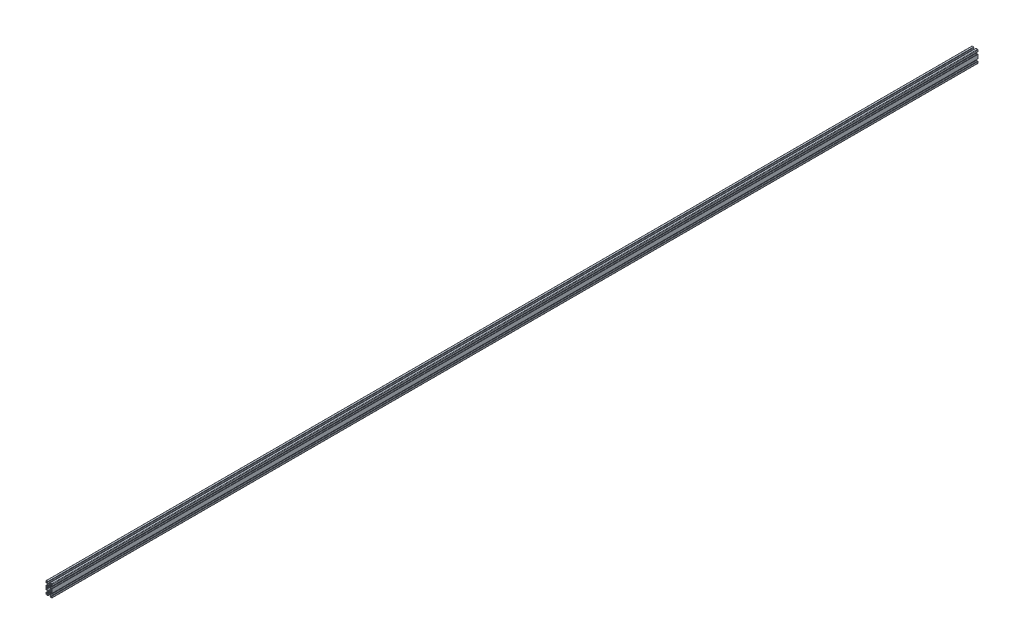
SolidWorks part; units mm, degrees
material "6061 Alloy"
ref_plane "Front Plane" through (0, 0, 0) normal (0, 0, 1) x (1, 0, 0)
ref_plane "Top Plane" through (0, 0, 0) normal (0, 1, 0) x (1, 0, 0)
ref_plane "Right Plane" through (0, 0, 0) normal (1, 0, 0) x (0, 0, -1)
sketch "Sketch1" plane through (0, 0, 0) normal (0, 0, 1) x (1, 0, 0)
  line L0 (10, -3.75) -> (10, -8.5)
  line L1 (8.5, -3.55) -> (8.5, -5.5)
  line L2 (9.5, -3.25) -> (9.5, -3.35)
  line L3 (9.7, -3.55) -> (9.8, -3.55)
  line L4 (9, -3.05) -> (9.3, -3.05)
  line L5 (9.7, 3.45) -> (9.8, 3.45)
  line L6 (9.5, 3.15) -> (9.5, 3.25)
  line L7 (9, 2.95) -> (9.3, 2.95)
  line L8 (8.5, 3.45) -> (8.5, 5.5)
  line L9 (10, 3.65) -> (10, 10)
  line L10 (-9.7, 3.45) -> (-9.8, 3.45)
  line L11 (-9.5, 3.15) -> (-9.5, 3.25)
  line L12 (-9, 2.95) -> (-9.3, 2.95)
  line L13 (-8.5, 3.45) -> (-8.5, 5.5)
  line L14 (-10, 3.65) -> (-10, 10)
  line L15 (-9.7, -3.55) -> (-9.8, -3.55)
  line L16 (-9.5, -3.25) -> (-9.5, -3.35)
  line L17 (-9, -3.05) -> (-9.3, -3.05)
  line L18 (-8.5, -3.55) -> (-8.5, -5.5)
  line L19 (-10, -3.75) -> (-10, -8.5)
  line L20 (-3.7, -10) -> (-8.5, -10)
  line L21 (-3.5, -8.5) -> (-5.5, -8.5)
  line L22 (-3.2, -9.5) -> (-3.3, -9.5)
  line L23 (-3.5, -9.7) -> (-3.5, -9.8)
  line L24 (-3, -9) -> (-3, -9.3)
  line L25 (3.7, -10) -> (8.5, -10)
  line L26 (3.5, -9.7) -> (3.5, -9.8)
  line L27 (3.2, -9.5) -> (3.3, -9.5)
  line L28 (3, -9) -> (3, -9.3)
  line L29 (3.5, -8.5) -> (5.5, -8.5)
  line L30 (-9.7, 23.5) -> (-9.8, 23.5)
  line L31 (-9.5, 23.2) -> (-9.5, 23.3)
  line L32 (-9, 23) -> (-9.3, 23)
  line L33 (-8.5, 23.5) -> (-8.5, 25.55)
  line L34 (-10, 23.7) -> (-10, 28.5)
  line L35 (-9.7, 16.5) -> (-9.8, 16.5)
  line L36 (-9.5, 16.8) -> (-9.5, 16.7)
  line L37 (-9, 17) -> (-9.3, 17)
  line L38 (-8.5, 16.5) -> (-8.5, 14.55)
  line L39 (-10, 16.3) -> (-10, 10)
  line L40 (10, 16.3) -> (10, 10)
  line L41 (8.5, 16.5) -> (8.5, 14.5)
  line L42 (9.5, 16.8) -> (9.5, 16.7)
  line L43 (9.7, 16.5) -> (9.8, 16.5)
  line L44 (9, 17) -> (9.3, 17)
  line L45 (9.7, 23.5) -> (9.8, 23.5)
  line L46 (9.5, 23.2) -> (9.5, 23.3)
  line L47 (9, 23) -> (9.3, 23)
  line L48 (8.5, 23.5) -> (8.5, 25.5)
  line L49 (10, 23.7) -> (10, 28.5)
  line L50 (-3.7, 30) -> (-8.5, 30)
  line L51 (-3.5, 28.5) -> (-5.5, 28.5)
  line L52 (-3, 29) -> (-3, 29.3)
  line L53 (-3.2, 29.5) -> (-3.3, 29.5)
  line L54 (-3.5, 29.7) -> (-3.5, 29.8)
  line L55 (3.7, 30) -> (8.5, 30)
  line L56 (3.5, 28.5) -> (5.5, 28.5)
  line L57 (3.2, 29.5) -> (3.3, 29.5)
  line L58 (3.5, 29.7) -> (3.5, 29.8)
  line L59 (3, 29) -> (3, 29.3)
  line L60 (2.4453, 18.7418) -> (2.9477, 18.1129)
  line L61 (1.2582, 17.5547) -> (1.8871, 17.0523)
  line L62 (-1.2582, 17.5547) -> (-1.8871, 17.0523)
  line L63 (-2.4453, 18.7418) -> (-2.9477, 18.1129)
  line L64 (-2.4453, 21.2582) -> (-2.9477, 21.8871)
  line L65 (-1.2582, 22.4453) -> (-1.8871, 22.9477)
  line L66 (3.5859, 24.6465) -> (5.8536, 26.9142)
  line L67 (4.6464, 23.5858) -> (6.9142, 25.8536)
  line L68 (4.5, 23.2322) -> (4.5, 20.9536)
  line L69 (4.4732, 20.8536) -> (4.0381, 20.1)
  line L70 (4.4732, 19.1464) -> (4.0381, 19.9)
  line L71 (4.5, 16.7678) -> (4.5, 19.0464)
  line L72 (7.2678, 26) -> (8, 26)
  line L73 (7.2678, 14) -> (8, 14)
  line L74 (2.4453, 21.2582) -> (2.9477, 21.8871)
  line L75 (4.6464, 16.4142) -> (6.9142, 14.1464)
  line L76 (3.2322, 15.5) -> (0.9536, 15.5)
  line L77 (0.8536, 15.5268) -> (0.1, 15.9619)
  line L78 (-0.8536, 15.5268) -> (-0.1, 15.9619)
  line L79 (-3.2322, 15.5) -> (-0.9536, 15.5)
  line L80 (3.5858, 15.3535) -> (6.2929, 12.6464)
  line L81 (-3.5858, 15.3535) -> (-6.2929, 12.6464)
  line L82 (-4.5, 16.7678) -> (-4.5, 19.0464)
  line L83 (-4.4732, 19.1464) -> (-4.0381, 19.9)
  line L84 (-4.4732, 20.8536) -> (-4.0381, 20.1)
  line L85 (-4.5, 23.2322) -> (-4.5, 20.9536)
  line L86 (-7.2178, 14.05) -> (-8, 14.05)
  line L87 (-7.3178, 26.05) -> (-8, 26.05)
  line L88 (-4.6464, 16.4142) -> (-6.8642, 14.1964)
  line L89 (-4.6464, 23.5858) -> (-6.9642, 25.9036)
  line L90 (1.2582, 22.4453) -> (1.8871, 22.9477)
  line L91 (-3.5859, 24.6465) -> (-5.8536, 26.9142)
  line L92 (6, 27.2678) -> (6, 28)
  line L93 (-6, 27.2678) -> (-6, 28)
  line L94 (3.2323, 24.5) -> (0.9537, 24.5)
  line L95 (0.8537, 24.4733) -> (0.1, 24.0381)
  line L96 (-0.8537, 24.4733) -> (-0.1, 24.0381)
  line L97 (-3.2323, 24.5) -> (-0.9537, 24.5)
  line L98 (-3.2322, -4.5) -> (-0.9536, -4.5)
  line L99 (-0.8536, -4.4732) -> (-0.1, -4.0381)
  line L100 (0.8536, -4.4732) -> (0.1, -4.0381)
  line L101 (3.2322, -4.5) -> (0.9536, -4.5)
  line L102 (-6, -7.2678) -> (-6, -8)
  line L103 (6, -7.2678) -> (6, -8)
  line L104 (-3.5858, -4.6464) -> (-5.8536, -6.9142)
  line L105 (1.2582, -2.4453) -> (1.8871, -2.9477)
  line L106 (-4.6464, -3.5858) -> (-6.9142, -5.8536)
  line L107 (-4.6464, 3.5858) -> (-6.9142, 5.8536)
  line L108 (-7.2678, -6) -> (-8, -6)
  line L109 (-7.2678, 6) -> (-8, 6)
  line L110 (-4.5, -3.2322) -> (-4.5, -0.9536)
  line L111 (-4.4732, -0.8536) -> (-4.0381, -0.1)
  line L112 (-4.4732, 0.8536) -> (-4.0381, 0.1)
  line L113 (-4.5, 3.2322) -> (-4.5, 0.9536)
  line L114 (-3.586, 4.6466) -> (-6.2929, 7.3535)
  line L115 (3.586, 4.6466) -> (6.2929, 7.3535)
  line L116 (-3.2324, 4.5001) -> (-0.9538, 4.5001)
  line L117 (-0.8538, 4.4733) -> (-0.1, 4.0381)
  line L118 (0.8538, 4.4733) -> (0.1, 4.0381)
  line L119 (3.2324, 4.5001) -> (0.9538, 4.5001)
  line L120 (4.6464, 3.5858) -> (6.9142, 5.8536)
  line L121 (2.4453, -1.2582) -> (2.9477, -1.8871)
  line L122 (7.2678, 6) -> (8, 6)
  line L123 (7.2678, -6) -> (8, -6)
  line L124 (4.5, 3.2322) -> (4.5, 0.9536)
  line L125 (4.4732, 0.8536) -> (4.0381, 0.1)
  line L126 (4.4732, -0.8536) -> (4.0381, -0.1)
  line L127 (4.5, -3.2322) -> (4.5, -0.9536)
  line L128 (4.6464, -3.5858) -> (6.9142, -5.8536)
  line L129 (3.5858, -4.6464) -> (5.8536, -6.9142)
  line L130 (-1.2582, -2.4453) -> (-1.8871, -2.9477)
  line L131 (-2.4453, -1.2582) -> (-2.9477, -1.8871)
  line L132 (-2.4453, 1.2582) -> (-2.9477, 1.8871)
  line L133 (-1.2582, 2.4453) -> (-1.8871, 2.9477)
  line L134 (1.2582, 2.4453) -> (1.8871, 2.9477)
  line L135 (2.4453, 1.2582) -> (2.9477, 1.8871)
  line L136 (6.6464, 12.5) -> (8, 12.5)
  line L137 (8.5, 8) -> (8.5, 12)
  line L138 (6.6464, 7.5) -> (8, 7.5)
  line L139 (-6.6464, 7.5) -> (-8, 7.5)
  line L140 (-8.5, 8) -> (-8.5, 12)
  line L141 (-6.6464, 12.5) -> (-8, 12.5)
  line L142 (0, 33.3296) -> (0, -13.4112) construction
  line L143 (-17.1897, 10) -> (16.9575, 10) construction
  line L144 (-17.1897, 0) -> (16.9575, 0) construction
  line L145 (-17.1897, 20) -> (16.9575, 20) construction
  arc A0 (9.5, -3.25) -> (9.3, -3.05) centre (9.3, -3.25) ccw
  arc A1 (10, -3.75) -> (9.8, -3.55) centre (9.8, -3.75) ccw
  arc A2 (9.5, -3.35) -> (9.7, -3.55) centre (9.7, -3.35) ccw
  arc A3 (9, -3.05) -> (8.5, -3.55) centre (9, -3.55) ccw
  arc A4 (9.7, 3.45) -> (9.5, 3.25) centre (9.7, 3.25) ccw
  arc A5 (9.8, 3.45) -> (10, 3.65) centre (9.8, 3.65) ccw
  arc A6 (9.3, 2.95) -> (9.5, 3.15) centre (9.3, 3.15) ccw
  arc A7 (8.5, 3.45) -> (9, 2.95) centre (9, 3.45) ccw
  arc A8 (-9.5, 3.25) -> (-9.7, 3.45) centre (-9.7, 3.25) ccw
  arc A9 (-10, 3.65) -> (-9.8, 3.45) centre (-9.8, 3.65) ccw
  arc A10 (-9.5, 3.15) -> (-9.3, 2.95) centre (-9.3, 3.15) ccw
  arc A11 (-9, 2.95) -> (-8.5, 3.45) centre (-9, 3.45) ccw
  arc A12 (-9.7, -3.55) -> (-9.5, -3.35) centre (-9.7, -3.35) ccw
  arc A13 (-9.8, -3.55) -> (-10, -3.75) centre (-9.8, -3.75) ccw
  arc A14 (-9.3, -3.05) -> (-9.5, -3.25) centre (-9.3, -3.25) ccw
  arc A15 (-8.5, -3.55) -> (-9, -3.05) centre (-9, -3.55) ccw
  arc A16 (-3.2, -9.5) -> (-3, -9.3) centre (-3.2, -9.3) ccw
  arc A17 (-3.7, -10) -> (-3.5, -9.8) centre (-3.7, -9.8) ccw
  arc A18 (-3.3, -9.5) -> (-3.5, -9.7) centre (-3.3, -9.7) ccw
  arc A19 (-3, -9) -> (-3.5, -8.5) centre (-3.5, -9) ccw
  arc A20 (3.5, -9.7) -> (3.3, -9.5) centre (3.3, -9.7) ccw
  arc A21 (3.5, -9.8) -> (3.7, -10) centre (3.7, -9.8) ccw
  arc A22 (3, -9.3) -> (3.2, -9.5) centre (3.2, -9.3) ccw
  arc A23 (3.5, -8.5) -> (3, -9) centre (3.5, -9) ccw
  arc A24 (-9.5, 23.3) -> (-9.7, 23.5) centre (-9.7, 23.3) ccw
  arc A25 (-10, 23.7) -> (-9.8, 23.5) centre (-9.8, 23.7) ccw
  arc A26 (-9.5, 23.2) -> (-9.3, 23) centre (-9.3, 23.2) ccw
  arc A27 (-9, 23) -> (-8.5, 23.5) centre (-9, 23.5) ccw
  arc A28 (-9.7, 16.5) -> (-9.5, 16.7) centre (-9.7, 16.7) ccw
  arc A29 (-9.8, 16.5) -> (-10, 16.3) centre (-9.8, 16.3) ccw
  arc A30 (-9.3, 17) -> (-9.5, 16.8) centre (-9.3, 16.8) ccw
  arc A31 (-8.5, 16.5) -> (-9, 17) centre (-9, 16.5) ccw
  arc A32 (9.5, 16.8) -> (9.3, 17) centre (9.3, 16.8) ccw
  arc A33 (10, 16.3) -> (9.8, 16.5) centre (9.8, 16.3) ccw
  arc A34 (9.5, 16.7) -> (9.7, 16.5) centre (9.7, 16.7) ccw
  arc A35 (9, 17) -> (8.5, 16.5) centre (9, 16.5) ccw
  arc A36 (9.7, 23.5) -> (9.5, 23.3) centre (9.7, 23.3) ccw
  arc A37 (9.8, 23.5) -> (10, 23.7) centre (9.8, 23.7) ccw
  arc A38 (9.3, 23) -> (9.5, 23.2) centre (9.3, 23.2) ccw
  arc A39 (8.5, 23.5) -> (9, 23) centre (9, 23.5) ccw
  arc A40 (-3, 29.3) -> (-3.2, 29.5) centre (-3.2, 29.3) ccw
  arc A41 (-3.5, 29.8) -> (-3.7, 30) centre (-3.7, 29.8) ccw
  arc A42 (-3.5, 29.7) -> (-3.3, 29.5) centre (-3.3, 29.7) ccw
  arc A43 (-3.5, 28.5) -> (-3, 29) centre (-3.5, 29) ccw
  arc A44 (3.2, 29.5) -> (3, 29.3) centre (3.2, 29.3) ccw
  arc A45 (3.7, 30) -> (3.5, 29.8) centre (3.7, 29.8) ccw
  arc A46 (3.3, 29.5) -> (3.5, 29.7) centre (3.3, 29.7) ccw
  arc A47 (3, 29) -> (3.5, 28.5) centre (3.5, 29) ccw
  arc A48 (2.4453, 18.7418) -> (2.4453, 21.2582) centre (0, 20) ccw
  arc A49 (-1.2582, 17.5547) -> (1.2582, 17.5547) centre (0, 20) ccw
  arc A50 (-2.4453, 21.2582) -> (-2.4453, 18.7418) centre (0, 20) ccw
  arc A51 (1.8871, 17.0523) -> (2.9477, 18.1129) centre (0, 20) ccw
  arc A52 (-2.9477, 18.1129) -> (-1.8871, 17.0523) centre (0, 20) ccw
  arc A53 (-1.8871, 22.9477) -> (-2.9477, 21.8871) centre (0, 20) ccw
  arc A54 (2.9477, 21.8871) -> (1.8871, 22.9477) centre (0, 20) ccw
  arc A55 (4.0381, 20.1) -> (4.0381, 19.9) centre (4.2113, 20) ccw
  arc A56 (4.5, 19.0464) -> (4.4732, 19.1464) centre (4.3, 19.0464) ccw
  arc A57 (4.4732, 20.8536) -> (4.5, 20.9536) centre (4.3, 20.9536) ccw
  arc A58 (6.9142, 14.1464) -> (7.2678, 14) centre (7.2678, 14.5) ccw
  arc A59 (4.5, 16.7678) -> (4.6464, 16.4142) centre (5, 16.7678) ccw
  arc A60 (4.6464, 23.5858) -> (4.5, 23.2322) centre (5, 23.2322) ccw
  arc A61 (7.2678, 26) -> (6.9142, 25.8536) centre (7.2678, 25.5) ccw
  arc A62 (0.1, 15.9619) -> (-0.1, 15.9619) centre (0, 15.7887) ccw
  arc A63 (-0.9536, 15.5) -> (-0.8536, 15.5268) centre (-0.9536, 15.7) ccw
  arc A64 (0.8536, 15.5268) -> (0.9536, 15.5) centre (0.9536, 15.7) ccw
  arc A65 (-3.2322, 15.5) -> (-3.5858, 15.3535) centre (-3.2322, 15) ccw
  arc A66 (3.5858, 15.3535) -> (3.2322, 15.5) centre (3.2322, 15) ccw
  arc A67 (-4.0381, 19.9) -> (-4.0381, 20.1) centre (-4.2113, 20) ccw
  arc A68 (-4.5, 20.9536) -> (-4.4732, 20.8536) centre (-4.3, 20.9536) ccw
  arc A69 (-4.4732, 19.1464) -> (-4.5, 19.0464) centre (-4.3, 19.0464) ccw
  arc A70 (-6.9642, 25.9036) -> (-7.3178, 26.05) centre (-7.3178, 25.55) ccw
  arc A71 (-4.5, 23.2322) -> (-4.6464, 23.5858) centre (-5, 23.2322) ccw
  arc A72 (-4.6464, 16.4142) -> (-4.5, 16.7678) centre (-5, 16.7678) ccw
  arc A73 (-7.2178, 14.05) -> (-6.8642, 14.1964) centre (-7.2178, 14.55) ccw
  arc A74 (-6, 27.2678) -> (-5.8536, 26.9142) centre (-5.5, 27.2678) ccw
  arc A75 (-3.5859, 24.6465) -> (-3.2323, 24.5) centre (-3.2323, 25) ccw
  arc A76 (3.2323, 24.5) -> (3.5859, 24.6465) centre (3.2323, 25) ccw
  arc A77 (5.8536, 26.9142) -> (6, 27.2678) centre (5.5, 27.2678) ccw
  arc A78 (8.5, 25.5) -> (8, 26) centre (8, 25.5) ccw
  arc A79 (10, 28.5) -> (8.5, 30) centre (8.5, 28.5) ccw
  arc A80 (8, 14) -> (8.5, 14.5) centre (8, 14.5) ccw
  arc A81 (-8.5, 14.55) -> (-8, 14.05) centre (-8, 14.55) ccw
  arc A82 (-8, 26.05) -> (-8.5, 25.55) centre (-8, 25.55) ccw
  arc A83 (6, 28) -> (5.5, 28.5) centre (5.5, 28) ccw
  arc A84 (-8.5, 30) -> (-10, 28.5) centre (-8.5, 28.5) ccw
  arc A85 (-5.5, 28.5) -> (-6, 28) centre (-5.5, 28) ccw
  arc A86 (-0.8537, 24.4733) -> (-0.9537, 24.5) centre (-0.9537, 24.3) ccw
  arc A87 (0.9537, 24.5) -> (0.8537, 24.4733) centre (0.9537, 24.3) ccw
  arc A88 (-0.1, 24.0381) -> (0.1, 24.0381) centre (0, 24.2113) ccw
  arc A89 (1.2582, 22.4453) -> (-1.2582, 22.4453) centre (0, 20) ccw
  arc A90 (-1.2582, -2.4453) -> (1.2582, -2.4453) centre (0, 0) ccw
  arc A91 (0.1, -4.0381) -> (-0.1, -4.0381) centre (0, -4.2113) ccw
  arc A92 (0.8536, -4.4732) -> (0.9536, -4.5) centre (0.9536, -4.3) ccw
  arc A93 (-0.9536, -4.5) -> (-0.8536, -4.4732) centre (-0.9536, -4.3) ccw
  arc A94 (-6, -8) -> (-5.5, -8.5) centre (-5.5, -8) ccw
  arc A95 (-10, -8.5) -> (-8.5, -10) centre (-8.5, -8.5) ccw
  arc A96 (5.5, -8.5) -> (6, -8) centre (5.5, -8) ccw
  arc A97 (-8.5, -5.5) -> (-8, -6) centre (-8, -5.5) ccw
  arc A98 (-8, 6) -> (-8.5, 5.5) centre (-8, 5.5) ccw
  arc A99 (8.5, 5.5) -> (8, 6) centre (8, 5.5) ccw
  arc A100 (8.5, -10) -> (10, -8.5) centre (8.5, -8.5) ccw
  arc A101 (8, -6) -> (8.5, -5.5) centre (8, -5.5) ccw
  arc A102 (6, -7.2678) -> (5.8536, -6.9142) centre (5.5, -7.2678) ccw
  arc A103 (3.5858, -4.6464) -> (3.2322, -4.5) centre (3.2322, -5) ccw
  arc A104 (-3.2322, -4.5) -> (-3.5858, -4.6464) centre (-3.2322, -5) ccw
  arc A105 (-5.8536, -6.9142) -> (-6, -7.2678) centre (-5.5, -7.2678) ccw
  arc A106 (-6.9142, 5.8536) -> (-7.2678, 6) centre (-7.2678, 5.5) ccw
  arc A107 (-4.5, 3.2322) -> (-4.6464, 3.5858) centre (-5, 3.2322) ccw
  arc A108 (-4.6464, -3.5858) -> (-4.5, -3.2322) centre (-5, -3.2322) ccw
  arc A109 (-7.2678, -6) -> (-6.9142, -5.8536) centre (-7.2678, -5.5) ccw
  arc A110 (-4.5, 0.9536) -> (-4.4732, 0.8536) centre (-4.3, 0.9536) ccw
  arc A111 (-4.4732, -0.8536) -> (-4.5, -0.9536) centre (-4.3, -0.9536) ccw
  arc A112 (-4.0381, -0.1) -> (-4.0381, 0.1) centre (-4.2113, 0) ccw
  arc A113 (3.2324, 4.5001) -> (3.586, 4.6466) centre (3.2324, 5.0001) ccw
  arc A114 (-3.586, 4.6466) -> (-3.2324, 4.5001) centre (-3.2324, 5.0001) ccw
  arc A115 (0.9538, 4.5001) -> (0.8538, 4.4733) centre (0.9538, 4.3001) ccw
  arc A116 (-0.8538, 4.4733) -> (-0.9538, 4.5001) centre (-0.9538, 4.3001) ccw
  arc A117 (-0.1, 4.0381) -> (0.1, 4.0381) centre (0, 4.2113) ccw
  arc A118 (6.9142, -5.8536) -> (7.2678, -6) centre (7.2678, -5.5) ccw
  arc A119 (4.5, -3.2322) -> (4.6464, -3.5858) centre (5, -3.2322) ccw
  arc A120 (4.6464, 3.5858) -> (4.5, 3.2322) centre (5, 3.2322) ccw
  arc A121 (7.2678, 6) -> (6.9142, 5.8536) centre (7.2678, 5.5) ccw
  arc A122 (4.5, -0.9536) -> (4.4732, -0.8536) centre (4.3, -0.9536) ccw
  arc A123 (4.4732, 0.8536) -> (4.5, 0.9536) centre (4.3, 0.9536) ccw
  arc A124 (4.0381, 0.1) -> (4.0381, -0.1) centre (4.2113, 0) ccw
  arc A125 (1.8871, -2.9477) -> (2.9477, -1.8871) centre (0, 0) ccw
  arc A126 (-2.9477, -1.8871) -> (-1.8871, -2.9477) centre (0, 0) ccw
  arc A127 (-1.8871, 2.9477) -> (-2.9477, 1.8871) centre (0, 0) ccw
  arc A128 (2.9477, 1.8871) -> (1.8871, 2.9477) centre (0, 0) ccw
  arc A129 (-2.4453, 1.2582) -> (-2.4453, -1.2582) centre (0, 0) ccw
  arc A130 (1.2582, 2.4453) -> (-1.2582, 2.4453) centre (0, 0) ccw
  arc A131 (2.4453, -1.2582) -> (2.4453, 1.2582) centre (0, 0) ccw
  arc A132 (-6.6464, 12.5) -> (-6.2929, 12.6464) centre (-6.6464, 13) ccw
  arc A133 (-8, 12.5) -> (-8.5, 12) centre (-8, 12) ccw
  arc A134 (-8.5, 8) -> (-8, 7.5) centre (-8, 8) ccw
  arc A135 (-6.2929, 7.3535) -> (-6.6464, 7.5) centre (-6.6464, 7) ccw
  arc A136 (6.2929, 12.6464) -> (6.6464, 12.5) centre (6.6464, 13) ccw
  arc A137 (8.5, 12) -> (8, 12.5) centre (8, 12) ccw
  arc A138 (8, 7.5) -> (8.5, 8) centre (8, 8) ccw
  arc A139 (6.6464, 7.5) -> (6.2929, 7.3535) centre (6.6464, 7) ccw
  dimension "D3" = 5.5
  dimension "D4" = 40
  dimension "D2" = 20
  dimension "D5" = 10
  dimension "D6" = 20
  dimension "D7" = 6
  dimension "D8" = 6
  dimension "D9" = 6
  dimension "D10" = 10
  dimension "D11" = 12
  dimension "D12" = 12
  dimension "D13" = 12
  dimension "D14" = 12
  dimension "D15" = 12
  dimension "D16" = 12
extrude "Extrude1" add sketch "Sketch1" along normal blind 3000
